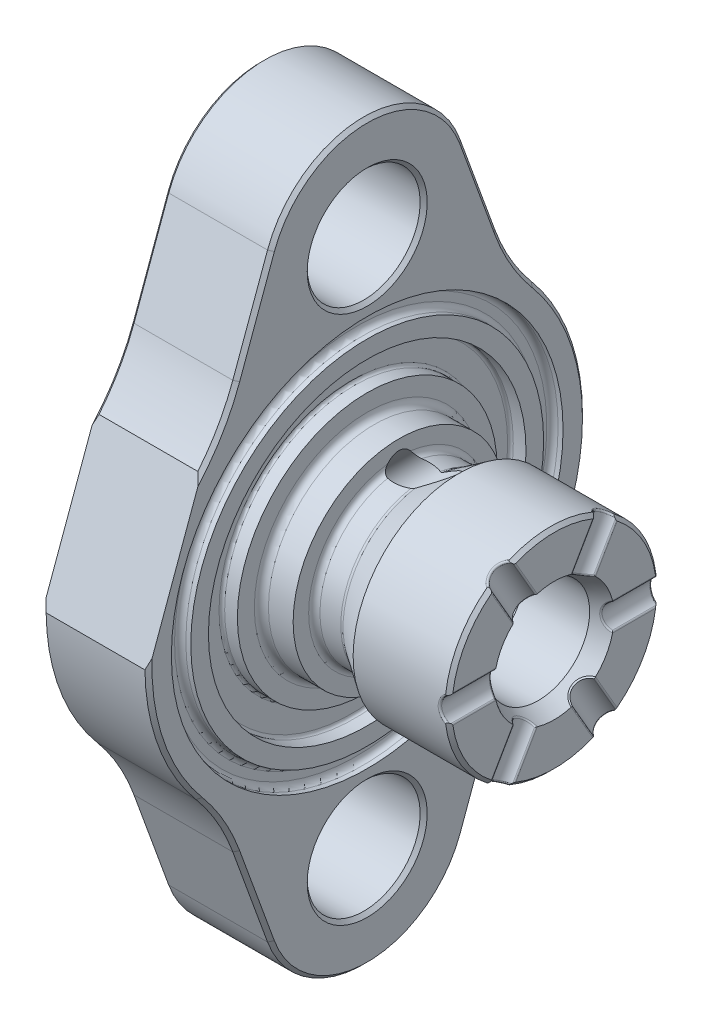
SolidWorks part; units mm, degrees
material "17CrNiMo6"
ref_plane "Front Plane" through (0, 0, 0) normal (0, 0, 1) x (1, 0, 0)
ref_plane "Top Plane" through (0, 0, 0) normal (0, 1, 0) x (1, 0, 0)
ref_plane "Right Plane" through (0, 0, 0) normal (1, 0, 0) x (0, 0, -1)
sketch "Sketch1" plane through (0, 0, 0) normal (0, 0, 1) x (1, 0, 0)
  line L0 (0, 0) -> (0, 52.5)
  line L1 (0, 52.5) -> (15, 52.5)
  line L2 (15, 52.5) -> (15, 27.75)
  line L3 (15, 27.75) -> (14.3, 27.75)
  line L4 (13.5, 26.95) -> (13.5, 25.8)
  line L5 (14.3, 25) -> (15, 25)
  line L6 (15, 25) -> (15, 22.5)
  line L7 (15, 22.5) -> (13.2, 22.5)
  line L8 (12.8, 22.1) -> (12.8, 18.8)
  line L9 (13.2, 18.4) -> (15, 18.4)
  line L10 (15, 18.4) -> (15, 15.9975)
  line L11 (16, 14.9975) -> (19.5, 14.9975)
  line L12 (19.5, 14.9975) -> (19.5, 12.8)
  line L13 (20.3, 12) -> (23.2579, 12)
  line L14 (23.7015, 12.1342) -> (28, 14.9975)
  line L15 (28, 14.9975) -> (41.5, 14.9975)
  line L16 (41.5, 14.9975) -> (41.5, 8.5)
  line L17 (41.5, 8.5) -> (39.25, 7.265)
  line L18 (39.25, 7.265) -> (30, 7.265)
  line L19 (30, 7.265) -> (30, 7.5)
  line L20 (30, 7.5) -> (28.5, 7.5)
  line L21 (28.5, 7.5) -> (27.9082, 6.515)
  line L22 (27.9082, 6.515) -> (13.5, 6.515)
  line L23 (13.5, 6.515) -> (13.5, 6.9)
  line L24 (11.5, 6.9) -> (7.3541, 0)
  line L25 (0, 0) -> (64.1591, 0) construction
  line L26 (13.5, 6.9) -> (11.5, 6.9)
  line L27 (0, 0) -> (7.3541, 0)
  arc A0 (13.5, 26.95) -> (14.3, 27.75) centre (14.3, 26.95) cw
  arc A1 (14.3, 25) -> (13.5, 25.8) centre (14.3, 25.8) cw
  arc A2 (13.2, 22.5) -> (12.8, 22.1) centre (13.2, 22.1) ccw
  arc A3 (13.2, 18.4) -> (12.8, 18.8) centre (13.2, 18.8) cw
  arc A4 (20.3, 12) -> (19.5, 12.8) centre (20.3, 12.8) cw
  arc A5 (23.7015, 12.1342) -> (23.2579, 12) centre (23.2579, 12.8) cw
  arc A6 (16, 14.9975) -> (15, 15.9975) centre (16, 15.9975) cw
  point P25 (21.5, 12)
  point P42 (23.5, 12)
  dimension "D29" = 0.8
  dimension "D30" = 1
  dimension "D31" = 0.4
  dimension "D32" = 0.8
  dimension "D1" = 59
  dimension "D2" = 15
  dimension "D3" = 105
  dimension "D4" = 11.5
  dimension "D5" = 14.53
  dimension "D6" = 13.8
  dimension "D7" = 15
  dimension "D8" = 29.995
  dimension "D9" = 24
  dimension "D10" = 26.5
  dimension "D11" = 13
  dimension "D12" = 59
  dimension "D13" = 2.25
  dimension "D14" = 17
  dimension "D15" = 13.03
  dimension "D16" = 30
  dimension "D17" = 22
  dimension "D18" = 13.5
  dimension "D19" = 18
  dimension "D20" = 36.8
  dimension "D21" = 45
  dimension "D22" = 50
  dimension "D23" = 55.5
  dimension "D24" = 1.5
  dimension "D25" = 2.2
  dimension "D26" = 2
  dimension "D27" = 41.5
  dimension "D28" = 28
revolve "Revolve1" add sketch "Sketch1" angle 360 about L25
sketch "Sketch2" plane through (0, 0, 0) normal (-1, 0, 0) x (0, 0, 1)
  line L0 (0, 0) -> (70.5057, 0) construction
  line L1 (0, 0) -> (0, 55.746) construction
  line L2 (13.6255, 42.4593) -> (18.5464, 28.9393)
  line L3 (-13.6255, 42.4593) -> (-18.5464, 28.9393)
  line L4 (13.6255, -42.4593) -> (18.5464, -28.9393)
  line L5 (-13.6255, -42.4593) -> (-18.5464, -28.9393)
  arc A0 (13.6255, 42.4593) -> (-13.6255, 42.4593) centre (0, 37.5) ccw
  arc A1 (23.7517, -19.9213) -> (23.7517, 19.9213) centre (0, 0) ccw
  arc A2 (23.7517, 19.9213) -> (18.5464, 28.9393) centre (46.7372, 39.1999) cw
  arc A3 (-23.7517, 19.9213) -> (-18.5464, 28.9393) centre (-46.7372, 39.1999) ccw
  arc A4 (-23.7517, -19.9213) -> (-23.7517, 19.9213) centre (0, 0) cw
  arc A5 (23.7517, -19.9213) -> (18.5464, -28.9393) centre (46.7372, -39.1999) ccw
  arc A6 (13.6255, -42.4593) -> (-13.6255, -42.4593) centre (0, -37.5) cw
  arc A7 (-23.7517, -19.9213) -> (-18.5464, -28.9393) centre (-46.7372, -39.1999) cw
  circle A8 centre (0, 37.5) radius 8 construction
  circle A9 centre (0, -37.5) radius 8 construction
  dimension "D1" = 29
  dimension "D2" = 62
  dimension "D3" = 75
  dimension "D5" = 30
  dimension "D6" = 104
  dimension "D7" = 16
  dimension "D8" = 91
  dimension "D4" = 20
extrude "Cut-Extrude1" cut sketch "Sketch2" against normal through all flip side to cut
sketch "Sketch3" plane through (0, 0, 0) normal (-1, 0, 0) x (0, 0, 1)
  circle A0 centre (0, 37.5) radius 8
  dimension "D1" = 16
extrude "Cut-Extrude2" cut sketch "Sketch3" against normal through all
mirror "Mirror1" about plane through (0, 0, 0) normal (0, 1, 0) of "Cut-Extrude2"
hole_wizard "Hole1" positions "Sketch7" profile "Sketch6" legacy
sketch "Sketch7" plane through (0, 0, 0) normal (-1, 0, 0) x (0, 0, 1)
  point P0 (0, 0)
sketch "Sketch6" plane through (0, 0, 0) normal (0, 1, 0) x (0, 0, 1)
  line L0 (0, 0) -> (0, 6.2017)
  line L1 (0, 6.2017) -> (2, 5)
  line L2 (2, 5) -> (2, 1.7321)
  line L3 (2, 1.7321) -> (3, 0)
  line L4 (3, 0) -> (0, 0)
  line L5 (0, -14.3089) -> (0, 102.4216) construction
  line L6 (0, 6.2017) -> (-2, 5) construction
  line L7 (-2, 1.7321) -> (-3, 0) construction
  dimension "Diameter" = 4
  dimension "Depth" = 5
  dimension "C-Sink Diameter" = 6
  dimension "C-Sink Angle" = 60
  dimension "Drill Angle" = 118
chamfer "Chamfer2" distance 0.5 angle 45 1 edges at (41.5, 0, 14.9975)
sketch "Sketch8" plane through (0, 0, 0) normal (0, 0, 1) x (1, 0, 0)
  line L0 (0, 0) -> (52.9452, 0) construction
  line L1 (41.5, -14.9975) -> (41.5, 14.9975) construction
  line L2 (45.4183, -2) -> (40.3, -2) construction
  line L3 (45.4183, -2) -> (45.4183, 2) construction
  line L4 (45.4183, 2) -> (40.3, 2) construction
  line L5 (40.3, -2) -> (40.3, 2) construction
  line L7 (41.5, 1.833) -> (44.8657, 1.833)
  line L8 (44.8657, 1.833) -> (44.8657, -1.833)
  line L9 (41.5, -1.833) -> (44.8657, -1.833)
  line L10 (41.5, -14.4975) -> (41.5, 14.4975) construction
  arc A0 (41.5, 1.833) -> (41.5, -1.833) centre (42.3, 0) ccw
  dimension "D4" = 2
  dimension "D5" = 1.2
  dimension "D1" = 4
  dimension "D2" = 2
  dimension "D3" = 1.2
  dimension "D7" = 3.3657
extrude "Cut-Extrude4" cut sketch "Sketch8" against normal through all
ref_axis "Axis1" through (30, 0, 0) along (1, 0, 0)
pattern_circular "CirPattern1" count 6 over 360 about axis through (30, 0, 0) along (1, 0, 0) of "Cut-Extrude4"
sketch "Sketch9" plane through (0, 0, 0) normal (-1, 0, 0) x (0, 0, 1)
  line L0 (12.5843, 50.2154) -> (38.1523, -20.0324)
  line L1 (38.1523, -20.0324) -> (42.1987, -18.5596)
  line L2 (42.1987, -18.5596) -> (16.6306, 51.6881)
  line L3 (16.6306, 51.6881) -> (12.5843, 50.2154)
  line L4 (0, 0) -> (50.117, 0) construction
  dimension "D1" = 70
  dimension "D2" = 29
extrude "Cut-Extrude5" cut sketch "Sketch9" against normal up to surface (15 mm away) up to face at (15, 37.5, 8)
ref_plane "Plane1" through (0, 0, 0) normal (0.7071, 0.7071, 0) x (0, 0, -1)
ref_plane "Plane2" through (16.75, 16.75, 0) normal (0.7071, 0.7071, 0) x (0, 0, -1)
sketch "Sketch10" plane through (16.75, 16.75, 0) normal (0.7071, 0.7071, 0) x (0, 0, -1)
  circle A0 centre (0, -6.7175) radius 2.5
  dimension "D1" = 5
extrude "Cut-Extrude6" cut sketch "Sketch10" against normal blind 12 and the other way through all
pattern_circular "CirPattern2" count 2 over 360 about axis through (30, 0, 0) along (1, 0, 0) of "Cut-Extrude6"
sketch "Sketch13" plane through (0, 0, 0) normal (-1, 0, 0) x (0, 0, 1)
  line L0 (0, 18.9466) -> (0, -21.9396) construction
  line L1 (4.9962, 8.7339) -> (4.9962, -7.6503) construction
  text T0 "7372 2964 01 - M\r\n11111 -  XX" font "Century Gothic" height 3.5
  line B0 (4.9962, -4.4157) -> (4.9962, 0.1601)
  line B1 (5.9289, -3.7379) -> (5.9289, -0.3703)
  line B2 (5.1362, 0.0805) -> (5.7889, -0.2907)
  line B3 (9.8181, -1.6011) -> (9.8181, -0.803)
  line B4 (12.9876, 0.1601) -> (9.8181, -1.6011)
  line B5 (5.9289, -3.7379) -> (8.9351, -2.0797)
  line B6 (8.9351, -5.7609) -> (8.2121, -6.1792)
  line B7 (12.9876, -2.0855) -> (12.9876, 0.1601)
  line B8 (9.8181, -5.2793) -> (8.9351, -5.7609)
  line B9 (9.8181, -5.2793) -> (11.8573, -4.07)
  line B10 (4.9962, 0.1601) -> (4.9962, 3.6565)
  line B11 (8.453, 1.6908) -> (4.9962, 3.6565)
  line B12 (9.0756, -5.5569) -> (9.6781, -5.1996)
  line B13 (12.8476, -2.0855) -> (12.8476, -0.0779)
  line B14 (12.8476, -0.0779) -> (9.8181, -1.7612)
  line B15 (9.6781, -0.803) -> (9.6781, -5.1996)
  line B16 (8.3806, 1.5709) -> (5.1362, 3.4158)
  line B17 (5.1362, 0.2415) -> (5.1362, 3.4158)
  line B18 (9.0756, -1.9986) -> (9.0756, -5.5569)
  line B19 (5.1362, 0.2415) -> (9.0756, -1.9986)
  line B20 (8.9351, -5.5991) -> (8.1394, -6.0595)
  line B21 (5.1362, -4.4157) -> (5.1362, 0.0805)
  line B22 (9.8181, -1.7612) -> (9.8181, -5.1166)
  line B23 (9.8181, -5.1166) -> (11.7859, -3.9496)
  line B24 (5.7889, -3.9751) -> (5.7889, -0.2907)
  line B25 (5.7889, -3.9751) -> (8.9351, -2.2396)
  line B26 (8.9351, -2.2396) -> (8.9351, -5.5991)
  line B27 (5.9289, -0.3703) -> (8.9351, -2.0797)
  arc B28 (11.8573, -4.07) -> (12.9876, -2.0855) centre (10.6804, -2.0855) ccw
  arc B29 (4.9962, -4.4157) -> (8.2121, -6.1792) centre (7.0876, -4.4157) ccw
  arc B30 (9.8181, -0.803) -> (8.453, 1.6908) centre (6.8575, -0.803) ccw
  arc B31 (11.7859, -3.9496) -> (12.8476, -2.0855) centre (10.6804, -2.0855) ccw
  arc B32 (9.6781, -0.803) -> (8.3806, 1.5709) centre (6.8575, -0.803) ccw
  arc B33 (5.1362, -4.4157) -> (8.1394, -6.0595) centre (7.0876, -4.4157) ccw
sketch_block_instance "SKETCH LOGO-1"
sketch_block "SKETCH LOGO" parameters "D1"=29.059, "D2"=11.4163, "D3"=29.624, "D4"=6.8884
extrude "Extrude1" cut sketch "Sketch13" against normal blind 0.1
chamfer "Chamfer3" distance 0.5 angle 45 28 edges at (15, -10.7756, 29.0669) (15, -24.2028, 20.7548) (15, -35.6993, 16.086) (15, -52, 0) (15, -35.6993, -16.086) (15, -24.2028, -20.7548) (15, 0, -31) (15, 24.3744, 20.6565) (15, 24.2028, -20.7548) (15, 35.6993, 16.086) (15, 35.6993, -16.086) (15, 52, 0) (15, 37.5, 8) (15, -37.5, 8) (0, -37.5, 8) (0, 37.5, 8) (0, -10.7756, 29.0669) (0, 24.3744, 20.6565) (0, -24.2028, 20.7548) (0, 35.6993, 16.086) (0, -35.6993, 16.086) (0, 52, 0) (0, -52, 0) (0, 35.6993, -16.086) (0, -35.6993, -16.086) (0, 24.2028, -20.7548) (0, -24.2028, -20.7548) (0, 0, -31)
fillet "Fillet1" radius 0.25 36 edges at (41.5, -1.833, -11.3406) (40.3114, 0.2136, -7.8447) (40.322, -0.2958, -14.9946) (41.5, 1.833, -11.3406) (41.5, -10.7377, -4.0828) (40.3114, -6.6869, -4.1074) (40.3, -12.985, -7.5043) (40.3114, 6.9005, -3.7373) (40.3504, 13.2055, -7.1091) (41.5, -8.9047, 7.2577) (40.3114, -6.9005, 3.7373) (40.3, -12.9914, 7.4932) (41.5, 1.833, 11.3406) (40.3114, -0.2136, 7.8447) (40.313, -0.2274, 14.9958) (41.5, 10.7377, 4.0828) (40.3114, 6.6869, 4.1074) (40.3, 12.985, 7.5043) (41.5, -8.9047, -7.2577) (41.5, 8.9047, -7.2577) (41.5, -10.7377, 4.0828) (41.5, -1.833, 11.3406) (41.5, 8.9047, 7.2577) (41.5, 10.7377, -4.0828)
